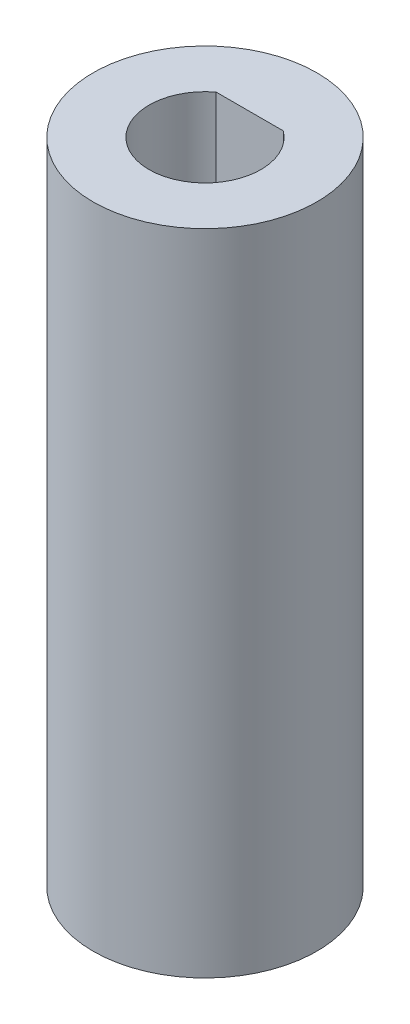
SolidWorks part; units mm, degrees
ref_plane "Front Plane" through (0, 0, 0) normal (0, 0, 1) x (1, 0, 0)
ref_plane "Top Plane" through (0, 0, 0) normal (0, 1, 0) x (1, 0, 0)
ref_plane "Right Plane" through (0, 0, 0) normal (1, 0, 0) x (0, 0, -1)
sketch "Sketch2" plane through (0, 0, 0) normal (0, 1, 0) x (1, 0, 0)
  line L0 (-1.5, 2) -> (1.5, 2)
  arc A0 (1.5, 2) -> (-1.5, 2) centre (0, 0) ccw
  circle A1 centre (0, 0) radius 2.5
  circle A2 centre (0, 0) radius 5
  point P4 (30.8499, -6.4239)
  point P6 (0, 0)
  dimension "D2" = 5
  dimension "D1" = 3
  dimension "D3" = 2.5
extrude "Boss-Extrude1" add sketch "Sketch2" along normal blind 29 contours A2 A1 A0 | L0 A0
